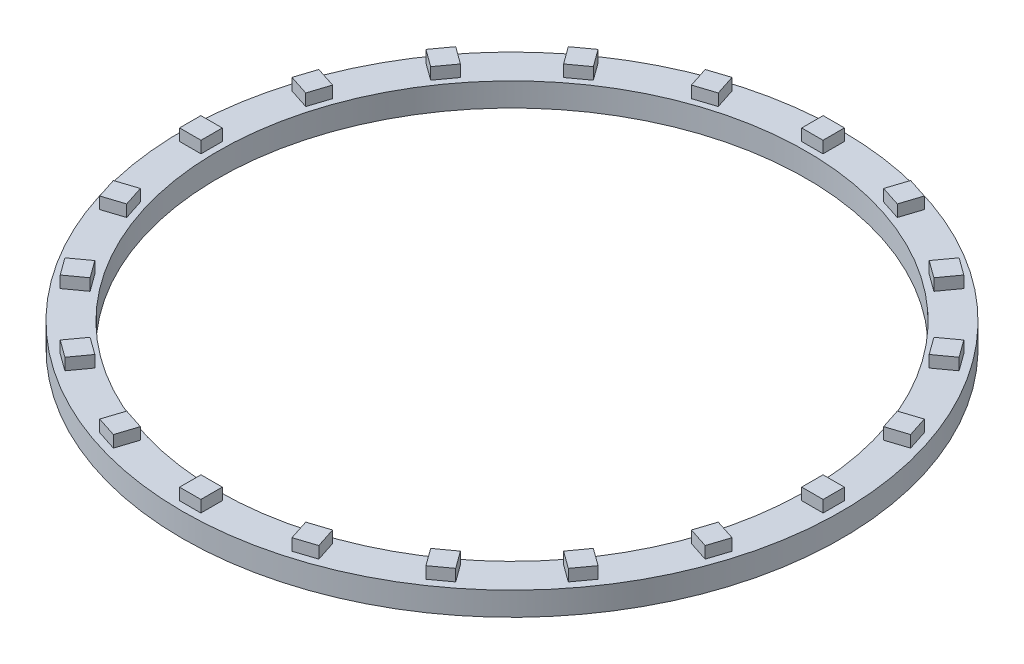
SolidWorks part; units mm, degrees
ref_plane "前视基准面" through (0, 0, 0) normal (0, 0, 1) x (1, 0, 0)
ref_plane "上视基准面" through (0, 0, 0) normal (0, 1, 0) x (1, 0, 0)
ref_plane "右视基准面" through (0, 0, 0) normal (1, 0, 0) x (0, 0, -1)
sketch "草图1" plane through (0, 0, 0) normal (0, 1, 0) x (1, 0, 0)
  circle A0 centre (0, 0) radius 28
  circle A1 centre (0, 0) radius 25
extrude "凸台-拉伸1" add sketch "草图1" along normal blind 2
sketch "草图2" plane through (0, 2, 0) normal (0, 1, 0) x (1, 0, 0)
  line L0 (7.5877, 26.2801) -> (9.3085, 25.721)
  line L1 (-0.9047, 27.3386) -> (0.9047, 27.3386)
  line L2 (-0.9047, 27.3386) -> (-0.9047, 25.5187)
  line L3 (-0.9047, 25.5187) -> (0.9047, 25.5187)
  line L4 (0.9047, 27.3386) -> (0.9047, 25.5187)
  line L5 (-0.9047, 27.3386) -> (0.9047, 25.5187) construction
  line L6 (-0.9047, 25.5187) -> (0.9047, 27.3386) construction
  line L7 (7.5877, 26.2801) -> (7.0253, 24.5493)
  line L8 (7.0253, 24.5493) -> (8.7461, 23.9901)
  line L9 (9.3085, 25.721) -> (8.7461, 23.9901)
  line L10 (15.3373, 22.6492) -> (16.8011, 21.5856)
  line L11 (15.3373, 22.6492) -> (14.2676, 21.1768)
  line L12 (14.2676, 21.1768) -> (15.7314, 20.1133)
  line L13 (16.8011, 21.5856) -> (15.7314, 20.1133)
  line L14 (21.5856, 16.8011) -> (22.6492, 15.3373)
  line L15 (21.5856, 16.8011) -> (20.1133, 15.7314)
  line L16 (20.1133, 15.7314) -> (21.1768, 14.2676)
  line L17 (22.6492, 15.3373) -> (21.1768, 14.2676)
  line L18 (25.721, 9.3085) -> (26.2801, 7.5877)
  line L19 (25.721, 9.3085) -> (23.9901, 8.7461)
  line L20 (23.9901, 8.7461) -> (24.5493, 7.0253)
  line L21 (26.2801, 7.5877) -> (24.5493, 7.0253)
  line L22 (27.3386, 0.9047) -> (27.3386, -0.9047)
  line L23 (27.3386, 0.9047) -> (25.5187, 0.9047)
  line L24 (25.5187, 0.9047) -> (25.5187, -0.9047)
  line L25 (27.3386, -0.9047) -> (25.5187, -0.9047)
  line L26 (26.2801, -7.5877) -> (25.721, -9.3085)
  line L27 (26.2801, -7.5877) -> (24.5493, -7.0253)
  line L28 (24.5493, -7.0253) -> (23.9901, -8.7461)
  line L29 (25.721, -9.3085) -> (23.9901, -8.7461)
  line L30 (22.6492, -15.3373) -> (21.5856, -16.8011)
  line L31 (22.6492, -15.3373) -> (21.1768, -14.2676)
  line L32 (21.1768, -14.2676) -> (20.1133, -15.7314)
  line L33 (21.5856, -16.8011) -> (20.1133, -15.7314)
  line L34 (16.8011, -21.5856) -> (15.3373, -22.6492)
  line L35 (16.8011, -21.5856) -> (15.7314, -20.1133)
  line L36 (15.7314, -20.1133) -> (14.2676, -21.1768)
  line L37 (15.3373, -22.6492) -> (14.2676, -21.1768)
  line L38 (9.3085, -25.721) -> (7.5877, -26.2801)
  line L39 (9.3085, -25.721) -> (8.7461, -23.9901)
  line L40 (8.7461, -23.9901) -> (7.0253, -24.5493)
  line L41 (7.5877, -26.2801) -> (7.0253, -24.5493)
  line L42 (0.9047, -27.3386) -> (-0.9047, -27.3386)
  line L43 (0.9047, -27.3386) -> (0.9047, -25.5187)
  line L44 (0.9047, -25.5187) -> (-0.9047, -25.5187)
  line L45 (-0.9047, -27.3386) -> (-0.9047, -25.5187)
  line L46 (-7.5877, -26.2801) -> (-9.3085, -25.721)
  line L47 (-7.5877, -26.2801) -> (-7.0253, -24.5493)
  line L48 (-7.0253, -24.5493) -> (-8.7461, -23.9901)
  line L49 (-9.3085, -25.721) -> (-8.7461, -23.9901)
  line L50 (-15.3373, -22.6492) -> (-16.8011, -21.5856)
  line L51 (-15.3373, -22.6492) -> (-14.2676, -21.1768)
  line L52 (-14.2676, -21.1768) -> (-15.7314, -20.1133)
  line L53 (-16.8011, -21.5856) -> (-15.7314, -20.1133)
  line L54 (-21.5856, -16.8011) -> (-22.6492, -15.3373)
  line L55 (-21.5856, -16.8011) -> (-20.1133, -15.7314)
  line L56 (-20.1133, -15.7314) -> (-21.1768, -14.2676)
  line L57 (-22.6492, -15.3373) -> (-21.1768, -14.2676)
  line L58 (-25.721, -9.3085) -> (-26.2801, -7.5877)
  line L59 (-25.721, -9.3085) -> (-23.9901, -8.7461)
  line L60 (-23.9901, -8.7461) -> (-24.5493, -7.0253)
  line L61 (-26.2801, -7.5877) -> (-24.5493, -7.0253)
  line L62 (-27.3386, -0.9047) -> (-27.3386, 0.9047)
  line L63 (-27.3386, -0.9047) -> (-25.5187, -0.9047)
  line L64 (-25.5187, -0.9047) -> (-25.5187, 0.9047)
  line L65 (-27.3386, 0.9047) -> (-25.5187, 0.9047)
  line L66 (-26.2801, 7.5877) -> (-25.721, 9.3085)
  line L67 (-26.2801, 7.5877) -> (-24.5493, 7.0253)
  line L68 (-24.5493, 7.0253) -> (-23.9901, 8.7461)
  line L69 (-25.721, 9.3085) -> (-23.9901, 8.7461)
  line L70 (-22.6492, 15.3373) -> (-21.5856, 16.8011)
  line L71 (-22.6492, 15.3373) -> (-21.1768, 14.2676)
  line L72 (-21.1768, 14.2676) -> (-20.1133, 15.7314)
  line L73 (-21.5856, 16.8011) -> (-20.1133, 15.7314)
  line L74 (-16.8011, 21.5856) -> (-15.3373, 22.6492)
  line L75 (-16.8011, 21.5856) -> (-15.7314, 20.1133)
  line L76 (-15.7314, 20.1133) -> (-14.2676, 21.1768)
  line L77 (-15.3373, 22.6492) -> (-14.2676, 21.1768)
  line L78 (-9.3085, 25.721) -> (-7.5877, 26.2801)
  line L79 (-9.3085, 25.721) -> (-8.7461, 23.9901)
  line L80 (-8.7461, 23.9901) -> (-7.0253, 24.5493)
  line L81 (-7.5877, 26.2801) -> (-7.0253, 24.5493)
  point P0 (0, 26.4286)
  point P84 (0, 0)
  dimension "D1" = 20
extrude "凸台-拉伸2" add sketch "草图2" along normal blind 1
